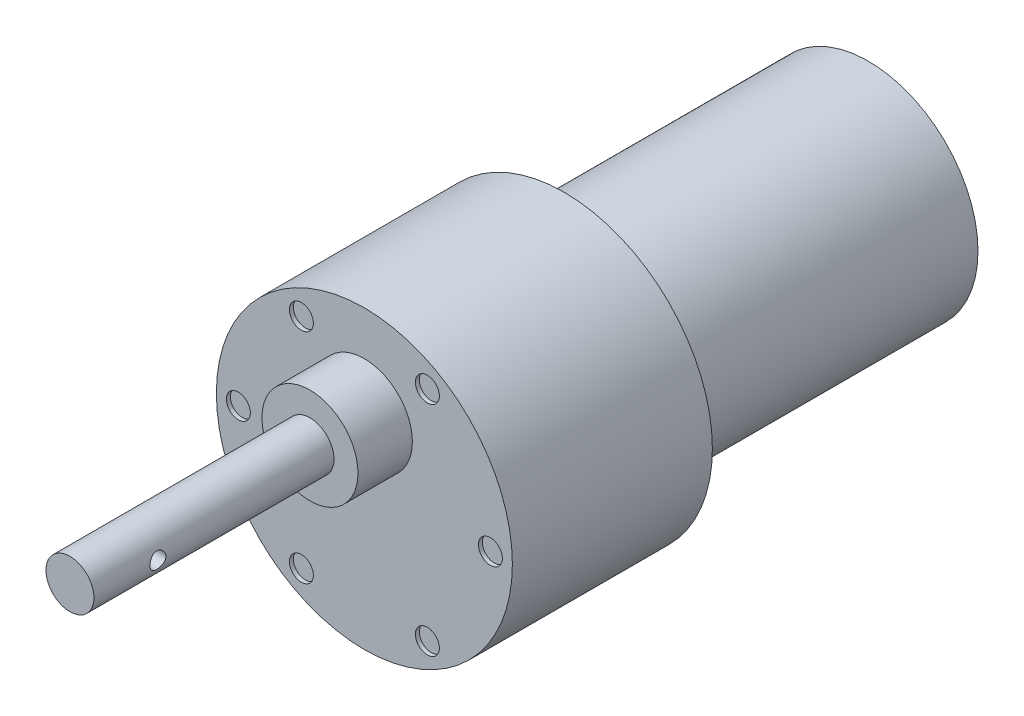
SolidWorks part; units mm, degrees
material "Custom Plastic"
ref_plane "Front Plane" through (0, 0, 0) normal (0, 0, 1) x (1, 0, 0)
ref_plane "Top Plane" through (0, 0, 0) normal (0, 1, 0) x (1, 0, 0)
ref_plane "Right Plane" through (0, 0, 0) normal (1, 0, 0) x (0, 0, -1)
sketch "Sketch1" plane through (0, 0, 0) normal (0, 0, 1) x (1, 0, 0)
  circle A0 centre (0, 0) radius 13.7
  dimension "D1" = 27.4
extrude "Boss-Extrude1" add sketch "Sketch1" along normal blind 38
sketch "Sketch2" plane through (0, 0, 38) normal (0, 0, 1) x (1, 0, 0)
  circle A0 centre (0, 0) radius 18.5
  dimension "D1" = 37
extrude "Boss-Extrude2" add sketch "Sketch2" along normal blind 25
sketch "Sketch3" plane through (0, 0, 63) normal (0, 0, 1) x (1, 0, 0)
  circle A0 centre (0, 7) radius 6
  dimension "D2" = 12
  dimension "D1" = 7
extrude "Boss-Extrude3" add sketch "Sketch3" along normal blind 6.8
sketch "Sketch4" plane through (0, 0, 69.8) normal (0, 0, 1) x (1, 0, 0)
  circle A0 centre (0, 7) radius 3
  dimension "D1" = 6
extrude "Boss-Extrude4" add sketch "Sketch4" along normal blind 30
sketch "Sketch5" plane through (0, 0, 63) normal (0, 0, 1) x (1, 0, 0)
  line L0 (0, 0) -> (-15.75, 0) construction
  circle A0 centre (-15.75, 0) radius 1.5
  circle A1 centre (-7.875, 13.6399) radius 1.5
  circle A2 centre (7.875, 13.6399) radius 1.5
  circle A3 centre (15.75, 0) radius 1.5
  circle A4 centre (7.875, -13.6399) radius 1.5
  circle A5 centre (-7.875, -13.6399) radius 1.5
  dimension "D2" = 3
  dimension "D1" = 15.75
  dimension "D4" = 15.75
  dimension "D3" = 6
extrude "Cut-Extrude1" cut sketch "Sketch5" against normal blind 0.5
sketch "Sketch6" plane through (0, 0, 0) normal (1, 0, 0) x (0, 0, -1)
  line L0 (-99.8, 10) -> (-99.8, 4) construction
  line L1 (-99.8, 10) -> (-99.8, 4) construction
  line L2 (-99.8, 4) -> (-69.8, 4) construction
  line L3 (-69.8, 10) -> (-99.8, 10) construction
  line L4 (-99.8, 4) -> (-69.8, 4) construction
  line L5 (-69.8, 10) -> (-99.8, 10)
  circle A0 centre (-91.8, 7) radius 1
  dimension "D1" = 2
  dimension "D2" = 8
  dimension "D3" = 3
extrude "Cut-Extrude2" cut sketch "Sketch6" against normal through all and the other way through all contours A0
